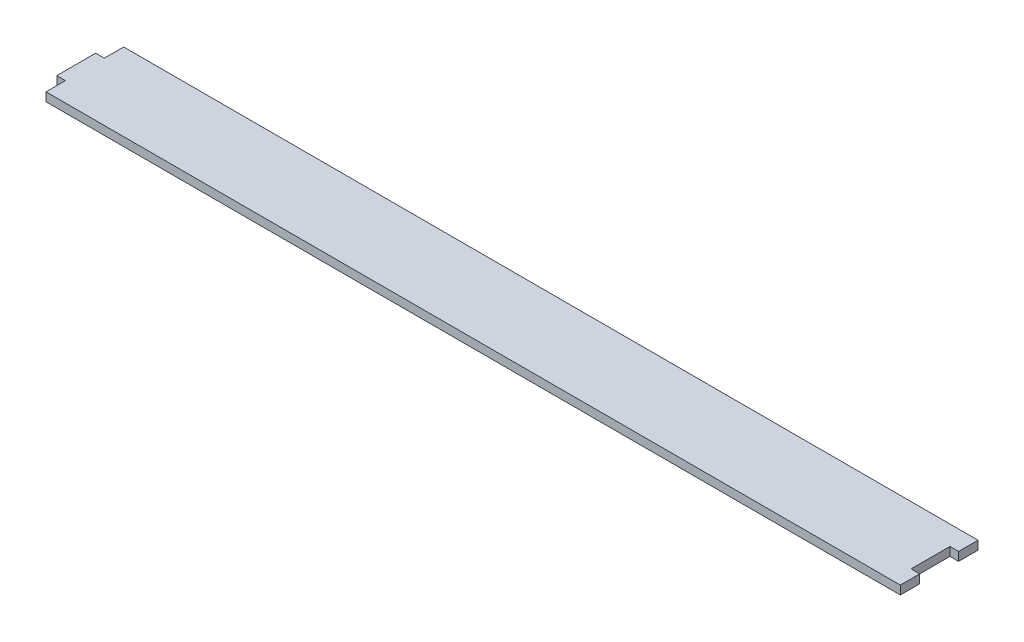
SolidWorks part; units mm, degrees
ref_plane "Front Plane" through (0, 0, 0) normal (0, 0, 1) x (1, 0, 0)
ref_plane "Top Plane" through (0, 0, 0) normal (0, 1, 0) x (1, 0, 0)
ref_plane "Right Plane" through (0, 0, 0) normal (1, 0, 0) x (0, 0, -1)
sketch "Sketch2" plane through (0, 0, 0) normal (0, 1, 0) x (1, 0, 0)
  line L0 (4, 27) -> (4, 36)
  line L1 (4, 0) -> (400, 0)
  line L3 (4, 36) -> (400, 36)
  line L4 (400, 0) -> (400, 9)
  line L5 (400, 27) -> (396, 27)
  line L7 (400, 9) -> (396, 9)
  line L8 (396, 27) -> (396, 9)
  line L9 (0, 27) -> (4, 27)
  line L11 (0, 9) -> (4, 9)
  line L13 (4, 9) -> (4, 0)
  line L14 (400, 27) -> (400, 36)
  line L15 (0, 27) -> (0, 9)
  dimension "D4" = 18
  dimension "D5" = 9
  dimension "D6" = 4
  dimension "D7" = 18
  dimension "D8" = 4
  dimension "D9" = 9
extrude "Boss-Extrude1" add sketch "Sketch2" along normal blind 4 contours L3 L14 L5 L8 L7 L4 L1 L13 L11 L15 L9 L0
